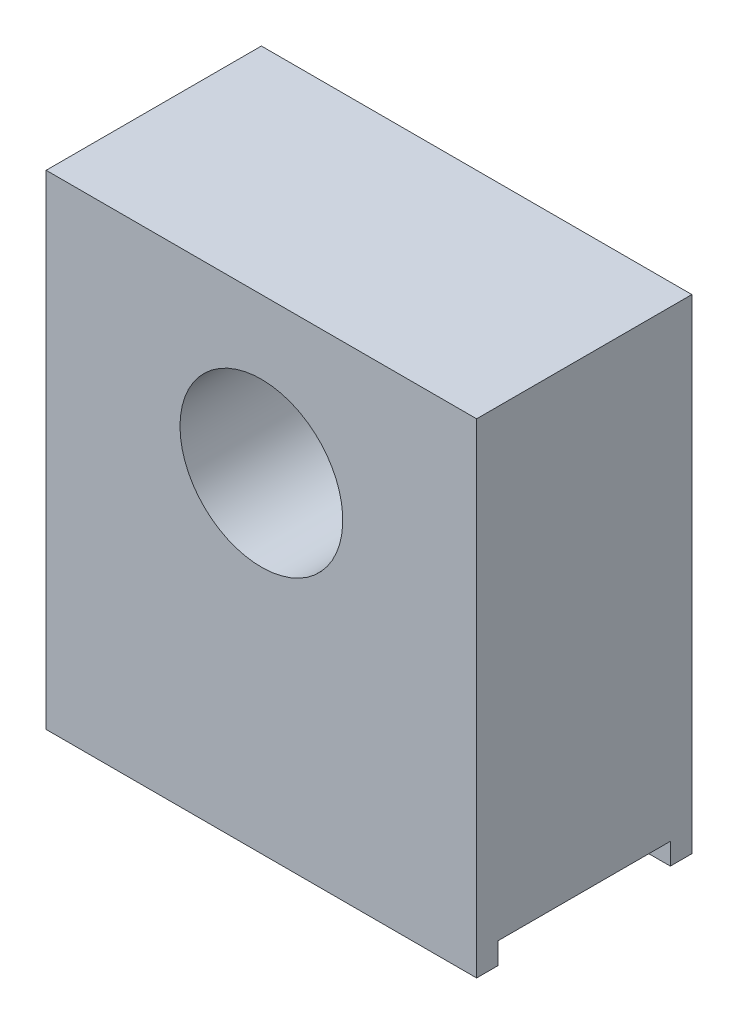
SolidWorks part; units mm, degrees
ref_plane "Front Plane" through (0, 0, 0) normal (0, 0, 1) x (1, 0, 0)
ref_plane "Top Plane" through (0, 0, 0) normal (0, 1, 0) x (1, 0, 0)
ref_plane "Right Plane" through (0, 0, 0) normal (1, 0, 0) x (0, 0, -1)
sketch "Sketch1" plane through (0, 0, 0) normal (0, 1, 0) x (1, 0, 0)
  line L1 (-14.6748, 6.8957) -> (17.3252, 6.8957)
  line L2 (-14.6748, 6.8957) -> (-14.6748, -9.1043)
  line L3 (-14.6748, -9.1043) -> (17.3252, -9.1043)
  line L4 (17.3252, 6.8957) -> (17.3252, -9.1043)
  dimension "D1" = 16
  dimension "D2" = 32
extrude "Boss-Extrude1" add sketch "Sketch1" along normal blind 36
sketch "Sketch2" plane through (0, 0, 0) normal (0, -1, 0) x (-1, 0, 0)
  line L0 (14.6748, 6.8957) -> (14.6748, -9.1043) construction
  line L1 (14.6748, 5.2957) -> (-17.3252, 5.2957)
  line L2 (14.6748, 5.2957) -> (14.6748, -7.5043)
  line L3 (14.6748, -7.5043) -> (-17.3252, -7.5043)
  line L4 (-17.3252, 5.2957) -> (-17.3252, -7.5043)
  line L5 (-17.3252, -9.1043) -> (-17.3252, 6.8957) construction
  line L6 (-17.3252, 6.8957) -> (14.6748, 6.8957) construction
  line L7 (14.6748, -9.1043) -> (-17.3252, -9.1043) construction
  dimension "D1" = 1.6
  dimension "D2" = 1.6
extrude "Cut-Extrude1" cut sketch "Sketch2" against normal blind 1.6
sketch "Sketch3" plane through (0, 0, -6.8957) normal (0, 0, -1) x (-1, 0, 0)
  line L0 (14.6748, 36) -> (14.6748, 0) construction
  line L1 (-17.3252, 0) -> (14.6748, 0) construction
  circle A0 centre (-1.3252, 24.5) radius 6.05
  dimension "D1" = 12.1
  dimension "D3" = 24.5
  dimension "D2" = 16
extrude "Cut-Extrude2" cut sketch "Sketch3" against normal through all
